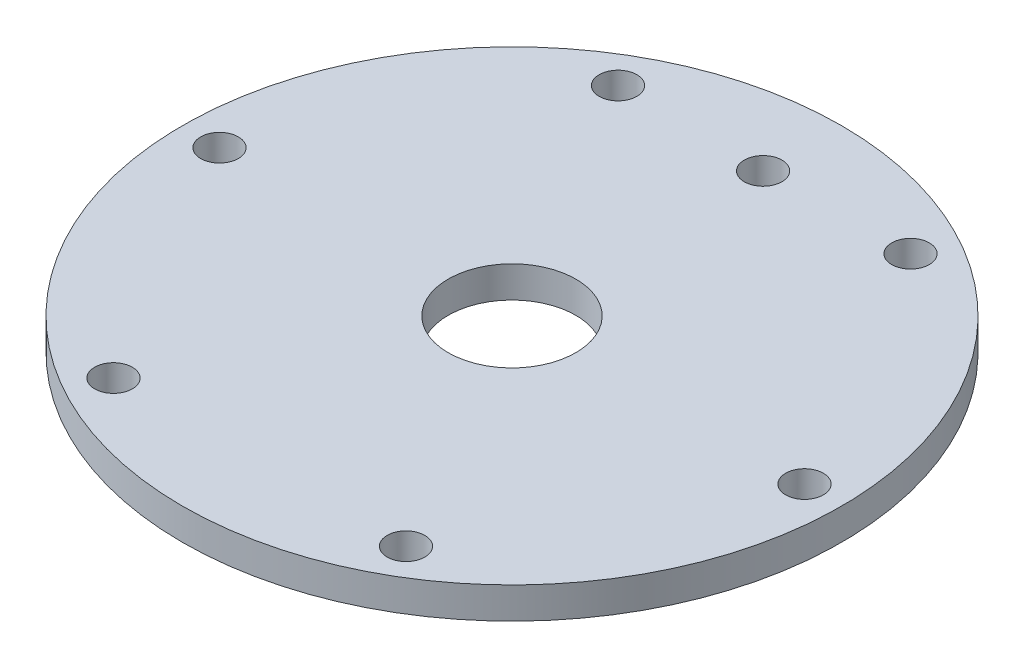
SolidWorks part; units mm, degrees
ref_plane "Front Plane" through (0, 0, 0) normal (0, 0, 1) x (1, 0, 0)
ref_plane "Top Plane" through (0, 0, 0) normal (0, 1, 0) x (1, 0, 0)
ref_plane "Right Plane" through (0, 0, 0) normal (1, 0, 0) x (0, 0, -1)
sketch "Sketch1" plane through (0, 0, 0) normal (0, 1, 0) x (1, 0, 0)
  circle A0 centre (0, 0) radius 105
  circle A1 centre (0, 0) radius 20.325
  dimension "D1" = 210
  dimension "D2" = 40.65
extrude "Boss-Extrude1" add sketch "Sketch1" along normal blind 10
sketch "Sketch2" plane through (0, 10, 0) normal (0, 1, 0) x (1, 0, 0)
  line L0 (0, 1.6884) -> (105, 0) construction
  circle A0 centre (0, 0) radius 105 construction
  circle A1 centre (93.0016, 0.1929) radius 6
  circle A4 centre (-46.3337, -80.6382) radius 6
  circle A5 centre (-46.6679, 80.4452) radius 6
  point P12 (0, 0)
  point P13 (0, 1.6884)
  dimension "D1" = 12
  dimension "D2" = 12
  dimension "D3" = 3
extrude "Cut-Extrude1" cut sketch "Sketch2" against normal blind 10
pattern_circular "CirPattern1" count 6 every 60 about axis through (0, 0, 0) along (0, 1, 0) of "Cut-Extrude1"
sketch "Sketch4" plane through (0, 10, 0) normal (0, 1, 0) x (1, 0, 0)
  line L0 (0, 0) -> (0, 127.8629) construction
  line L1 (0, 0) -> (46.3337, 80.6382) construction
  circle A0 centre (0, 80) radius 6
  circle A1 centre (0, 0) radius 20.325 construction
  dimension "D1" = 12
  dimension "D2" = 80
  dimension "D3" = 29.881
extrude "Cut-Extrude2" cut sketch "Sketch4" against normal blind 10
